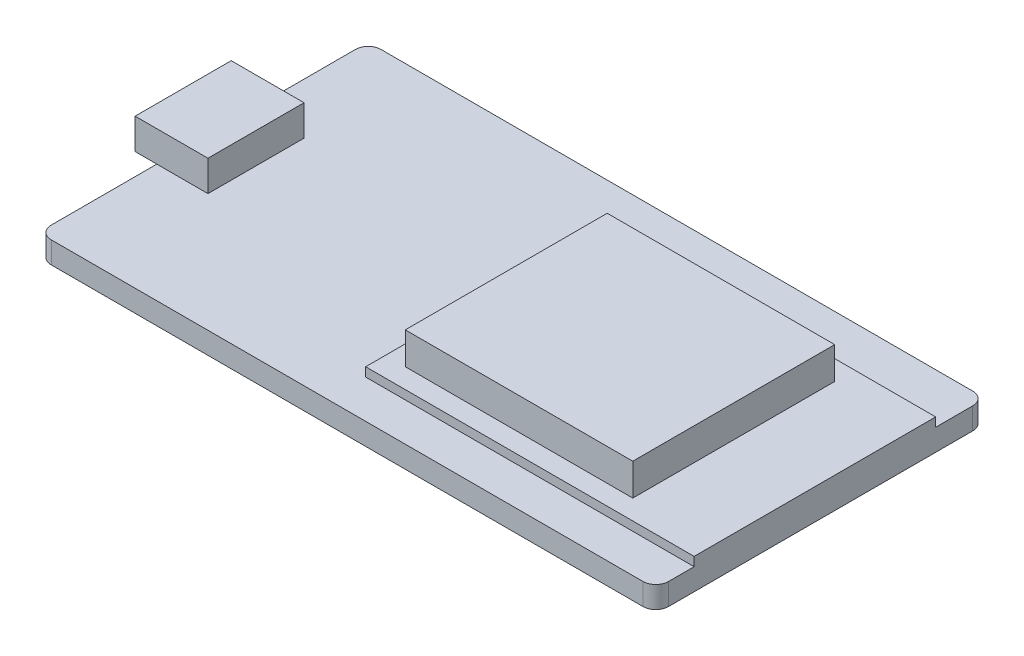
SolidWorks part; units mm, degrees
ref_plane "Alzado" through (0, 0, 0) normal (0, 0, 1) x (1, 0, 0)
ref_plane "Planta" through (0, 0, 0) normal (0, 1, 0) x (1, 0, 0)
ref_plane "Vista lateral" through (0, 0, 0) normal (1, 0, 0) x (0, 0, -1)
sketch "Croquis1" plane through (0, 0, 0) normal (0, 1, 0) x (1, 0, 0)
  line L1 (-24.15, 12.9) -> (24.15, 12.9)
  line L2 (-24.15, 12.9) -> (-24.15, -12.9)
  line L3 (-24.15, -12.9) -> (24.15, -12.9)
  line L4 (24.15, 12.9) -> (24.15, -12.9)
  line L5 (-24.15, 12.9) -> (24.15, -12.9) construction
  line L6 (-24.15, -12.9) -> (24.15, 12.9) construction
  point P0 (0, 0)
  dimension "D1" = 48.3
  dimension "D2" = 25.8
extrude "Saliente-Extruir1" add sketch "Croquis1" along normal blind 1.7
sketch "Croquis2" plane through (0, 1.7, 0) normal (0, 1, 0) x (1, 0, 0)
  line L0 (24.15, 12.9) -> (24.15, 9) construction
  line L1 (24.15, -12.9) -> (24.15, 12.9) construction
  line L3 (24.15, 9) -> (-1.55, 9)
  line L4 (24.15, 9) -> (24.15, -9.9)
  line L5 (24.15, -9.9) -> (-1.55, -9.9)
  line L6 (-1.55, 9) -> (-1.55, -9.9)
  dimension "D1" = 25.7
  dimension "D2" = 18.9
  dimension "D3" = 3.9
extrude "Saliente-Extruir2" add sketch "Croquis2" along normal blind 0.7
sketch "Croquis3" plane through (0, 2.4, 0) normal (0, 1, 0) x (1, 0, 0)
  line L0 (-1.55, 9) -> (-1.55, 7.45) construction
  line L1 (-1.55, 9) -> (-1.55, -9.9) construction
  line L3 (0, 7.45) -> (17.8, 7.45)
  line L5 (0, -8.35) -> (17.8, -8.35)
  line L6 (17.8, 7.45) -> (17.8, -8.35)
  line L7 (0, 7.45) -> (-1.55, 7.45) construction
  line L8 (0, 7.45) -> (0, -8.35)
  dimension "D1" = 19.35
  dimension "D2" = 15.8
  dimension "D3" = 1.55
  dimension "D4" = 1.55
extrude "Saliente-Extruir3" add sketch "Croquis3" along normal blind 2.5
sketch "Croquis4" plane through (0, 1.7, 0) normal (0, 1, 0) x (1, 0, 0)
  line L0 (-24.15, 12.9) -> (-24.15, 3.88) construction
  line L1 (-24.15, 12.9) -> (-24.15, -12.9) construction
  line L2 (-20.15, 3.88) -> (-25.85, 3.88)
  line L3 (-25.85, 3.88) -> (-25.85, -3.64)
  line L4 (-25.85, -3.64) -> (-20.15, -3.64)
  line L5 (-20.15, -3.64) -> (-20.15, 3.88)
  dimension "D1" = 9.02
  dimension "D2" = 1.7
  dimension "D3" = 5.7
  dimension "D4" = 7.52
extrude "Saliente-Extruir4" add sketch "Croquis4" along normal blind 2.4
fillet "Redondeo1" radius 1 4 edges at (24.15, 0.85, 12.9) (24.15, 0.85, -12.9) (-24.15, 0.85, -12.9) (-24.15, 0.85, 12.9)
sketch "Croquis5" plane through (0, 0, 0) normal (0, -1, 0) x (1, 0, 0)
  line L0 (24.15, 10.3) -> (-24.31, 10.3)
  line L2 (24.15, 11.9) -> (24.15, -11.9) construction
  line L3 (23.15, 12.9) -> (24.15, 12.9) construction
  line L4 (24.15, 12.9) -> (24.15, 10.3) construction
  line L5 (24.15, 0) -> (34.9783, 0) construction
  line L6 (-24.31, 10.3) -> (-24.31, 12.9)
  line L7 (-24.31, 12.9) -> (24.15, 12.9)
  line L8 (24.15, 12.9) -> (24.15, 10.3)
  line L9 (-24.31, -12.9) -> (24.15, -12.9)
  line L10 (-24.31, -10.3) -> (-24.31, -12.9)
  line L11 (24.15, -10.3) -> (-24.31, -10.3)
  line L12 (24.15, -12.9) -> (24.15, -10.3)
  point P12 (0, 0)
  dimension "D1" = 48.46
  dimension "D2" = 2.6
